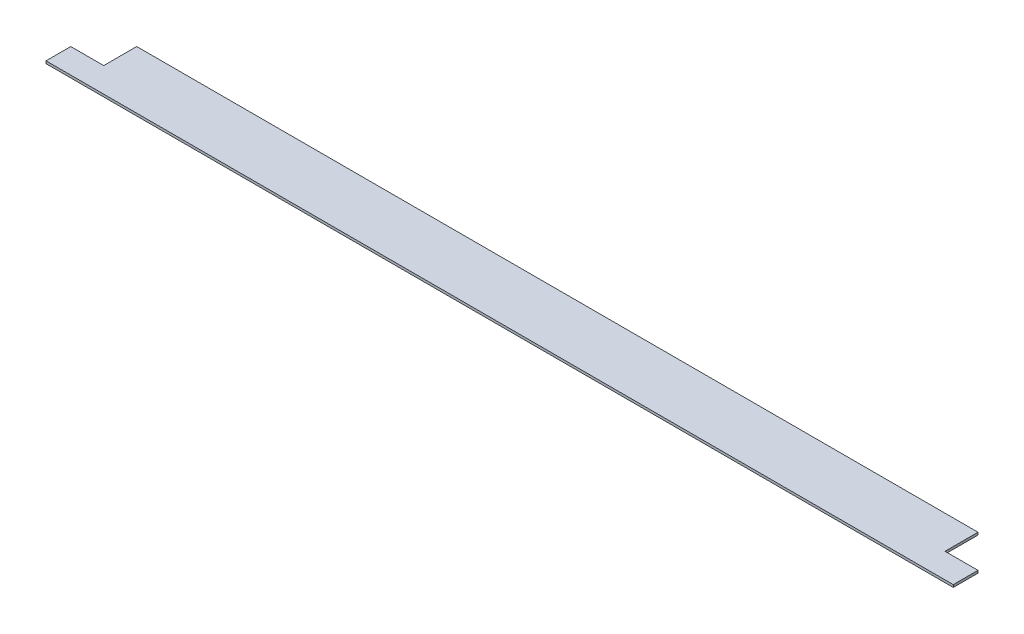
SolidWorks part; units mm, degrees
ref_plane "Alzado" through (0, 0, 0) normal (0, 0, 1) x (1, 0, 0)
ref_plane "Planta" through (0, 0, 0) normal (0, 1, 0) x (1, 0, 0)
ref_plane "Vista lateral" through (0, 0, 0) normal (1, 0, 0) x (0, 0, -1)
sketch "Croquis1" plane through (0, 0, 0) normal (0, 1, 0) x (1, 0, 0)
  line L1 (550, -35) -> (-550, -35)
  line L2 (550, -35) -> (550, 35)
  line L3 (550, 35) -> (-550, 35)
  line L4 (-550, -35) -> (-550, 35)
  line L5 (550, -35) -> (-550, 35) construction
  line L6 (550, 35) -> (-550, -35) construction
  point P0 (0, 0)
  dimension "D1" = 1100
  dimension "D2" = 70
extrude "Extruir1" add sketch "Croquis1" along normal blind 3
sketch "Croquis2" plane through (0, 3, 0) normal (0, 1, 0) x (1, 0, 0)
  line L0 (0, 35) -> (0, -35) construction
  line L1 (-550, 35) -> (-510, 35)
  line L2 (-550, 35) -> (-550, -5)
  line L3 (-550, -5) -> (-510, -5)
  line L4 (-510, 35) -> (-510, -5)
  line L5 (550, 35) -> (-550, 35) construction
  line L6 (-550, -35) -> (550, -35) construction
  line L7 (510, 35) -> (510, -5)
  line L8 (550, -5) -> (510, -5)
  line L9 (550, 35) -> (550, -5)
  line L10 (550, 35) -> (510, 35)
  dimension "D1" = 40
  dimension "D2" = 40
extrude "Extruir2" cut sketch "Croquis2" against normal blind 10
